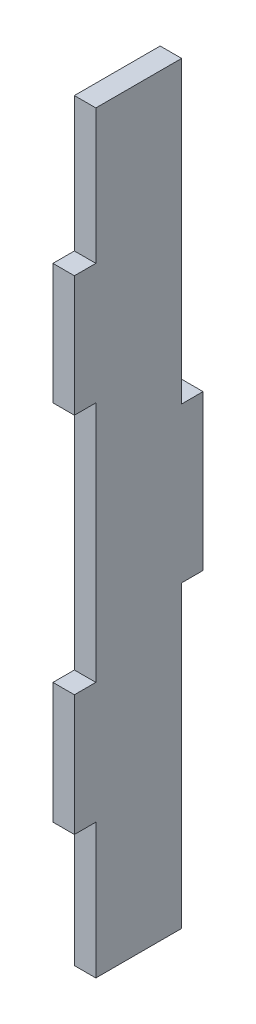
SolidWorks part; units mm, degrees
ref_plane "Front Plane" through (0, 0, 0) normal (0, 0, 1) x (1, 0, 0)
ref_plane "Top Plane" through (0, 0, 0) normal (0, 1, 0) x (1, 0, 0)
ref_plane "Right Plane" through (0, 0, 0) normal (1, 0, 0) x (0, 0, -1)
sketch "Sketch1" plane through (0, 0, 0) normal (1, 0, 0) x (0, 0, -1)
  line L1 (-9, 52.7) -> (9, 52.7)
  line L2 (-9, 52.7) -> (-9, -52.7)
  line L3 (-9, -52.7) -> (9, -52.7)
  line L4 (9, 52.7) -> (9, -52.7)
  line L5 (-9, 52.7) -> (9, -52.7) construction
  line L6 (-9, -52.7) -> (9, 52.7) construction
  point P0 (0, 0)
  dimension "D1" = 105.4
  dimension "D2" = 18
extrude "Boss-Extrude1" add sketch "Sketch1" along normal blind 3
sketch "Sketch3" plane through (3, 0, 0) normal (1, 0, 0) x (0, 0, -1)
  line L1 (9, -52.7) -> (6, -52.7)
  line L2 (9, -52.7) -> (9, -10.835)
  line L3 (9, -10.835) -> (6, -10.835)
  line L4 (6, -52.7) -> (6, -10.835)
  line L5 (9, 52.7) -> (6, 52.7)
  line L6 (9, 52.7) -> (9, 10.835)
  line L7 (9, 10.835) -> (6, 10.835)
  line L8 (6, 52.7) -> (6, 10.835)
  dimension "D1" = 3
  dimension "D2" = 3
  dimension "D3" = 41.865
  dimension "D4" = 41.865
extrude "Cut-Extrude2" cut sketch "Sketch3" against normal blind 3
sketch "Sketch5" plane through (0, 0, 0) normal (-1, 0, 0) x (0, 0, 1)
  line L0 (6, -16.89) -> (6, 16.97)
  line L1 (9, -52.7) -> (6, -52.7)
  line L2 (9, -52.7) -> (9, -33.82)
  line L3 (9, -33.82) -> (6, -33.82)
  line L4 (6, -52.7) -> (6, -33.82)
  line L5 (9, 52.7) -> (6, 52.7)
  line L6 (9, 52.7) -> (9, 33.87)
  line L7 (9, 33.87) -> (6, 33.87)
  line L8 (6, 52.7) -> (6, 33.87)
  line L9 (6, -16.89) -> (9, -16.89)
  line L10 (9, 52.7) -> (9, -52.7) construction
  line L11 (6, 16.97) -> (9, 16.97)
  line M10 (-6, -52.7) -> (9, -52.7)
  line M11 (9, -52.7) -> (9, 52.7)
  line M12 (9, 52.7) -> (-6, 52.7)
  dimension "D1" = 3
  dimension "D2" = 3
  dimension "D3" = 18.83
  dimension "D4" = 18.88
  dimension "D5" = 33.86
  dimension "D6" = 16.93
extrude "Cut-Extrude5" cut sketch "Sketch5" against normal blind 3 contours L4 L3 M10 M11 | L11 L0 L9 M11 | L8 L7 M12 M11
